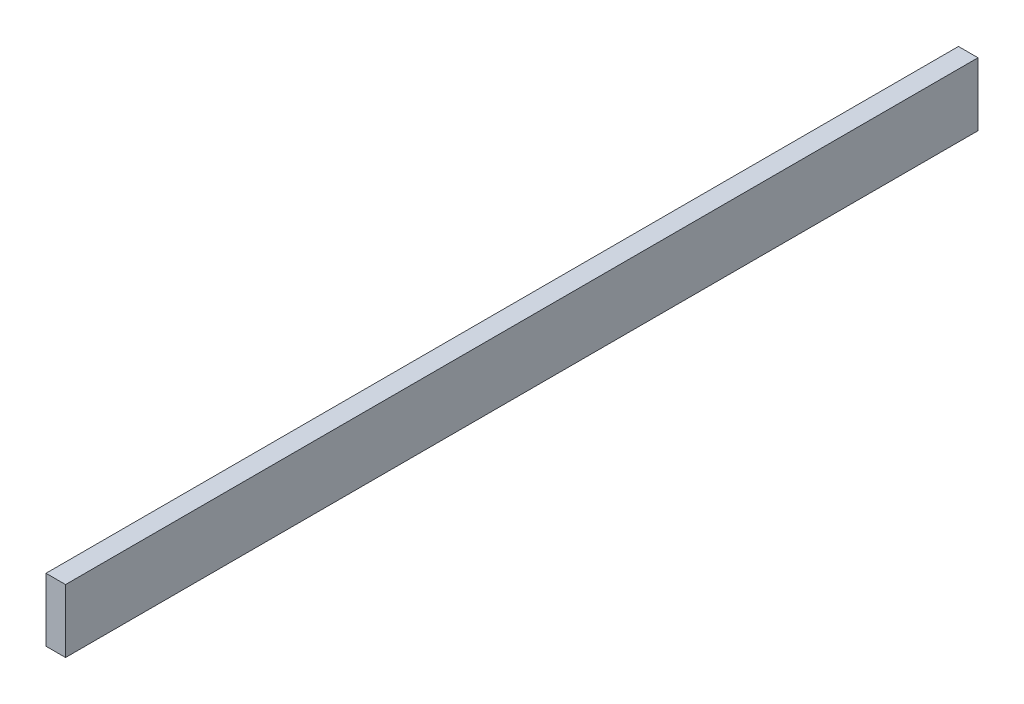
SolidWorks part; units mm, degrees
ref_plane "Front Plane" through (0, 0, 0) normal (0, 0, 1) x (1, 0, 0)
ref_plane "Top Plane" through (0, 0, 0) normal (0, 1, 0) x (1, 0, 0)
ref_plane "Right Plane" through (0, 0, 0) normal (1, 0, 0) x (0, 0, -1)
sketch "Sketch1" plane through (0, 0, 0) normal (0, 0, 1) x (1, 0, 0)
  line L1 (9, 29.1) -> (-9, 29.1)
  line L2 (9, 29.1) -> (9, -29.1)
  line L3 (9, -29.1) -> (-9, -29.1)
  line L4 (-9, 29.1) -> (-9, -29.1)
  line L5 (9, 29.1) -> (-9, -29.1) construction
  line L6 (9, -29.1) -> (-9, 29.1) construction
  point P0 (0, 0)
  dimension "D1" = 18
  dimension "D2" = 58.2
extrude "Boss-Extrude1" add sketch "Sketch1" along normal blind 840
